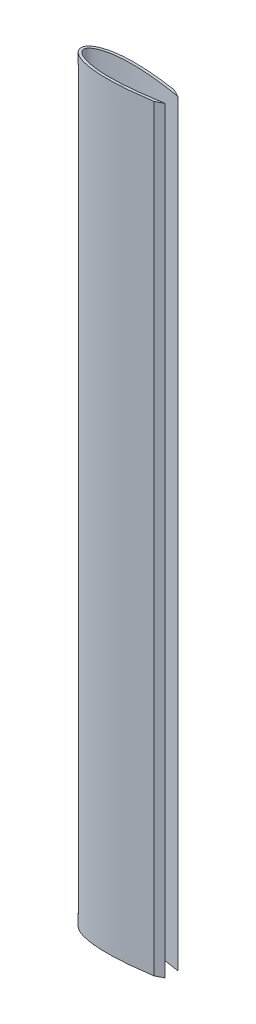
SolidWorks part; units mm, degrees
material "Thornel Mat VMA"
ref_plane "Front Plane" through (0, 0, 0) normal (0, 0, 1) x (1, 0, 0)
ref_plane "Top Plane" through (0, 0, 0) normal (0, 1, 0) x (1, 0, 0)
ref_plane "Right Plane" through (0, 0, 0) normal (1, 0, 0) x (0, 0, -1)
curve "Curve1"
  spline degree 3 poles (175, 0, 0.39) (172.0852, 0, 1.0915) (166.2645, 0, 2.4925) (154.6079, 0, 5.0916) (140.0384, 0, 8.0914) (122.535, 0, 11.2821) (105.0374, 0, 14.0632) (87.5357, 0, 16.3132) (70.0313, 0, 17.9205) (55.4197, 0, 18.4982) (43.7407, 0, 18.2589) (34.9709, 0, 17.6628) (26.1803, 0, 16.4887) (18.8668, 0, 14.856) (13.0461, 0, 12.9027) (8.5677, 0, 10.9406) (4.8376, 0, 8.56) (1.3515, 0, 5.1922) (-0.8999, 0, 0) (1.3515, 0, -5.1922) (4.8376, 0, -8.56) (8.5677, 0, -10.9406) (13.0461, 0, -12.9027) (18.8668, 0, -14.856) (26.1803, 0, -16.4887) (34.9709, 0, -17.6628) (43.7407, 0, -18.2589) (55.4197, 0, -18.4982) (70.0313, 0, -17.9205) (87.5357, 0, -16.3132) (105.0374, 0, -14.0632) (122.535, 0, -11.2821) (140.0384, 0, -8.0914) (154.6079, 0, -5.0916) (166.2645, 0, -2.4925) (172.0852, 0, -1.0915) (175, 0, -0.39) knots 0 0 0 0 0.024526 0.048978 0.0977 0.146209 0.194521 0.242629 0.29054 0.338291 0.362158 0.386079 0.410164 0.434658 0.44724 0.460337 0.474609 0.483094 0.5 0.516906 0.525391 0.539663 0.55276 0.565342 0.589836 0.613921 0.637842 0.661709 0.70946 0.757371 0.805479 0.853791 0.9023 0.951022 0.975474 1 1 1 1
sketch "Sketch2" plane through (0, 0, 0) normal (0, 1, 0) x (1, 0, 0)
  line L0 (129.4626, -10) -> (129.4626, 10)
  line L1 (0, 0) -> (40, 0) construction
  line L2 (128.8651, 6.6783) -> (129.4626, 6.5708)
  line L3 (128.8651, -6.6783) -> (129.4626, -6.5708)
  line L4 (128.4004, -4.0948) -> (119.4626, -4.0948)
  line L5 (128.4004, 4.0948) -> (119.4626, 4.0948)
  line L6 (119.4626, 4.0948) -> (119.4626, -4.0948)
  line L7 (116.4626, -6.1456) -> (116.4626, 6.1463)
  line L8 (128.4004, 4.0948) -> (129.4626, 4.0948)
  line L9 (128.4004, -4.0948) -> (129.4626, -4.0948)
  line L10 (109.4626, 13.3218) -> (119.4626, 8.3102)
  line L11 (109.4626, -13.3218) -> (119.4626, -8.3102)
  arc A0 (175, 0.39) -> (175, -0.39) centre (174.9061, 0) cw construction
  arc A1 (38.9143, 14.5244) -> (38.9143, -14.5244) centre (40, 0) ccw
  arc A2 (40, 11.9706) -> (40, -11.9706) centre (40, 0) ccw
  spline S0 degree 3 poles (1542.8809, -3734.4544) (469.6798, 145.9151) (323.9942, 32.6771) (154.6079, -5.0916) (140.0384, -8.0914) (122.535, -11.2821) (105.0374, -14.0632) (87.5357, -16.3132) (70.0313, -17.9205) (55.4197, -18.4982) (43.7407, -18.2589) (34.9709, -17.6628) (26.1803, -16.4887) (18.8668, -14.856) (13.0461, -12.9027) (8.5677, -10.9406) (4.8376, -8.56) (1.3515, -5.1922) (-0.8999, 0) (1.3515, 5.1922) (4.8376, 8.56) (8.5677, 10.9406) (13.0461, 12.9027) (18.8668, 14.856) (26.1803, 16.4887) (34.9709, 17.6628) (43.7407, 18.2589) (55.4197, 18.4982) (70.0313, 17.9205) (87.5357, 16.3132) (105.0374, 14.0632) (122.535, 11.2821) (140.0384, 8.0914) (154.6079, 5.0916) (323.9946, -32.6772) (469.6804, -145.9156) (1542.8876, 3734.4785) knots -1.32202 -1.32202 -1.32202 -1.32202 0.024526 0.048978 0.0977 0.146209 0.194521 0.242629 0.29054 0.338291 0.362158 0.386079 0.410164 0.434658 0.44724 0.460337 0.474609 0.483094 0.5 0.516906 0.525391 0.539663 0.55276 0.565342 0.589836 0.613921 0.637842 0.661709 0.70946 0.757371 0.805479 0.853791 0.9023 0.951022 0.975474 2.322023 2.322023 2.322023 2.322023 only from (175, -0.39) to (175, 0.39) construction
  spline S1 degree 3 poles (129.4626, -10) (127.1436, -10.4171) (119.0057, -11.8431) (105.0374, -14.0632) (87.5357, -16.3132) (70.0313, -17.9205) (55.4197, -18.4982) (43.7407, -18.2589) (34.9709, -17.6628) (26.1803, -16.4887) (18.8668, -14.856) (13.0461, -12.9027) (8.5677, -10.9406) (4.8376, -8.56) (1.3515, -5.1922) (-0.8999, 0) (1.3515, 5.1922) (4.8376, 8.56) (8.5677, 10.9406) (13.0461, 12.9027) (18.8668, 14.856) (26.1803, 16.4887) (34.9709, 17.6628) (43.7407, 18.2589) (55.4197, 18.4982) (70.0313, 17.9205) (87.5357, 16.3132) (105.0374, 14.0632) (119.0057, 11.8431) (127.1436, 10.4171) (129.4626, 10) knots 0.126933 0.126933 0.126933 0.126933 0.146209 0.194521 0.242629 0.29054 0.338291 0.362158 0.386079 0.410164 0.434658 0.44724 0.460337 0.474609 0.483094 0.5 0.516906 0.525391 0.539663 0.55276 0.565342 0.589836 0.613921 0.637842 0.661709 0.70946 0.757371 0.805479 0.853791 0.873067 0.873067 0.873067 0.873067
  spline S2 degree 3 poles (129.4626, 10) (132.9795, 9.3674) (142.3464, 7.6162) (154.6079, 5.0916) (166.2645, 2.4925) (172.0852, 1.0915) (175, 0.39) knots 0.873067 0.873067 0.873067 0.873067 0.9023 0.951022 0.975474 1 1 1 1 construction
  spline S3 degree 3 poles (175, -0.39) (172.0852, -1.0915) (166.2645, -2.4925) (154.6079, -5.0916) (142.3464, -7.6162) (132.9795, -9.3674) (129.4626, -10) knots 0 0 0 0 0.024526 0.048978 0.0977 0.126933 0.126933 0.126933 0.126933 construction
  spline S4 degree 1 poles (128.8651, -6.6783) (128.8651, 6.6783) knots 0 0 1 1 construction
  spline S5 degree 3 poles (128.8651, -6.6783) (123.2803, -7.6829) (112.0846, -9.5777) (95.2528, -11.9841) (78.3698, -13.8507) (61.4696, -15.0125) (49.0102, -15.0793) (40.8155, -14.6705) (37.5234, -14.4261) (33.1891, -14.0055) (27.5149, -13.2566) (21.28, -11.9716) (16.1096, -10.4044) (12.3688, -8.97) (9.4963, -7.5117) (7.4339, -6.1478) (6.0146, -5.0073) (4.9011, -3.8639) (4.0445, -2.5797) (3.5813, -1.4385) (3.4035, -0.5835) (3.3608, 0) (3.4035, 0.5835) (3.5813, 1.4385) (4.0445, 2.5797) (4.9011, 3.8639) (6.0146, 5.0073) (7.4339, 6.1478) (9.4963, 7.5117) (12.3688, 8.97) (16.1096, 10.4044) (21.28, 11.9716) (27.5149, 13.2566) (33.1891, 14.0055) (37.5234, 14.4261) (40.8155, 14.6705) (49.0102, 15.0793) (61.4696, 15.0125) (78.3698, 13.8507) (95.2528, 11.9841) (108.1539, 10.1397) (117.0027, 8.723) (122.5997, 7.7868) (126.5175, 7.1006) (128.8651, 6.6783) knots 0.126933 0.126933 0.126933 0.126933 0.173566 0.2202 0.266833 0.313466 0.3601 0.370224 0.381883 0.387712 0.406733 0.43005 0.441708 0.453367 0.465025 0.470854 0.476683 0.482512 0.488342 0.494171 0.497085 0.5 0.502915 0.505829 0.511658 0.517488 0.523317 0.529146 0.534975 0.546633 0.558292 0.56995 0.593267 0.612288 0.618117 0.629776 0.6399 0.686534 0.733167 0.7798 0.826434 0.840396 0.853465 0.873067 0.873067 0.873067 0.873067
  spline S6 degree 1 poles (128.4004, -4.0948) (128.4004, 4.0948) knots 0 0 1 1 construction
  spline S7 degree 3 poles (128.4004, -4.0948) (125.4208, -4.6307) (120.4449, -5.4961) (114.4717, -6.4736) (106.2964, -7.7542) (94.5243, -9.4235) (78.1296, -11.2364) (64.1525, -12.1952) (53.0352, -12.4335) (44.7322, -12.2885) (36.5047, -11.7721) (28.4281, -10.7646) (21.9019, -9.4173) (16.9572, -7.9176) (13.4135, -6.5576) (10.7902, -5.2197) (8.9797, -4.0225) (7.7551, -3.0335) (6.9401, -2.1875) (6.3723, -1.328) (6.0919, -0.6231) (6.009, -0.2025) (5.9955, 0) (6.009, 0.2025) (6.0919, 0.6231) (6.3723, 1.328) (6.9401, 2.1875) (7.7551, 3.0335) (8.9797, 4.0225) (10.7902, 5.2197) (13.4135, 6.5576) (16.9572, 7.9176) (21.9019, 9.4173) (28.2305, 10.7238) (34.0775, 11.4707) (38.6308, 11.8818) (41.5737, 12.0826) (46.5985, 12.3211) (53.0352, 12.4335) (64.1525, 12.1952) (78.1296, 11.2364) (94.9207, 9.3796) (111.6756, 6.9845) (122.8354, 5.0958) (128.4004, 4.0948) knots 0.126933 0.126933 0.126933 0.126933 0.151901 0.168546 0.176869 0.2202 0.266833 0.313466 0.336783 0.3601 0.383417 0.406733 0.43005 0.441708 0.453367 0.465025 0.470854 0.476683 0.482512 0.488342 0.494171 0.497085 0.5 0.502915 0.505829 0.511658 0.517488 0.523317 0.529146 0.534975 0.546633 0.558292 0.56995 0.593267 0.614819 0.620648 0.632306 0.6399 0.663217 0.686534 0.733167 0.7798 0.826434 0.873067 0.873067 0.873067 0.873067
  point P6 (129.4626, 0)
  point P19 (116.4626, -6.1456)
  point P24 (109.4626, 13.3218)
  point P27 (119.4626, 8.3102)
  dimension "D1" = 20
  dimension "D2" = 3
  dimension "D3" = 10
  dimension "D4" = 10
  dimension "D5" = 20
extrude "Boss-Extrude1" add sketch "Sketch2" along normal blind 1000 contours L3 S5 L2 L0 S1
